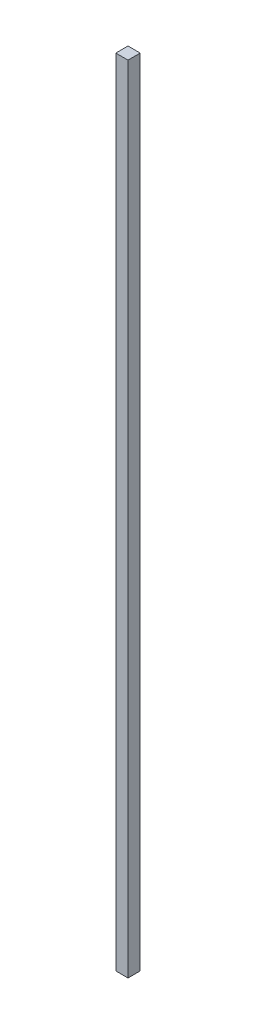
SolidWorks part; units mm, degrees
ref_plane "Front Plane" through (0, 0, 0) normal (0, 0, 1) x (1, 0, 0)
ref_plane "Top Plane" through (0, 0, 0) normal (0, 1, 0) x (1, 0, 0)
ref_plane "Right Plane" through (0, 0, 0) normal (1, 0, 0) x (0, 0, -1)
sketch "Sketch1" plane through (0, 0, 0) normal (0, 1, 0) x (1, 0, 0)
  line L0 (-8, 8) -> (8, 8)
  line L1 (-10, -10) -> (10, -10)
  line L2 (-10, -10) -> (-10, 10)
  line L3 (-10, 10) -> (10, 10)
  line L4 (10, -10) -> (10, 10)
  line L5 (-10, -10) -> (10, 10) construction
  line L6 (-10, 10) -> (10, -10) construction
  line L7 (8, -8) -> (8, 8)
  line L8 (-8, -8) -> (8, -8)
  line L9 (-8, -8) -> (-8, 8)
  point P0 (0, 0)
  dimension "D1" = 20
  dimension "D2" = 2
extrude "Boss-Extrude1" add sketch "Sketch1" along normal blind 1300
sketch "Sketch2" plane through (0, 1300, 0) normal (0, 1, 0) x (1, 0, 0)
  line L1 (-10, 10) -> (10, 10)
  line L2 (-10, 10) -> (-10, -10)
  line L3 (-10, -10) -> (10, -10)
  line L4 (10, 10) -> (10, -10)
extrude "Boss-Extrude2" add sketch "Sketch2" along normal blind 1
sketch "Sketch3" plane through (0, 0, 0) normal (0, -1, 0) x (1, 0, 0)
  line L0 (10, -10) -> (-10, -10) construction
  line L1 (-10, 10) -> (10, 10)
  line L2 (-10, 10) -> (-10, -10)
  line L3 (-10, -10) -> (10, -10)
  line L4 (10, 10) -> (10, -10)
extrude "Boss-Extrude3" add sketch "Sketch3" along normal blind 1
